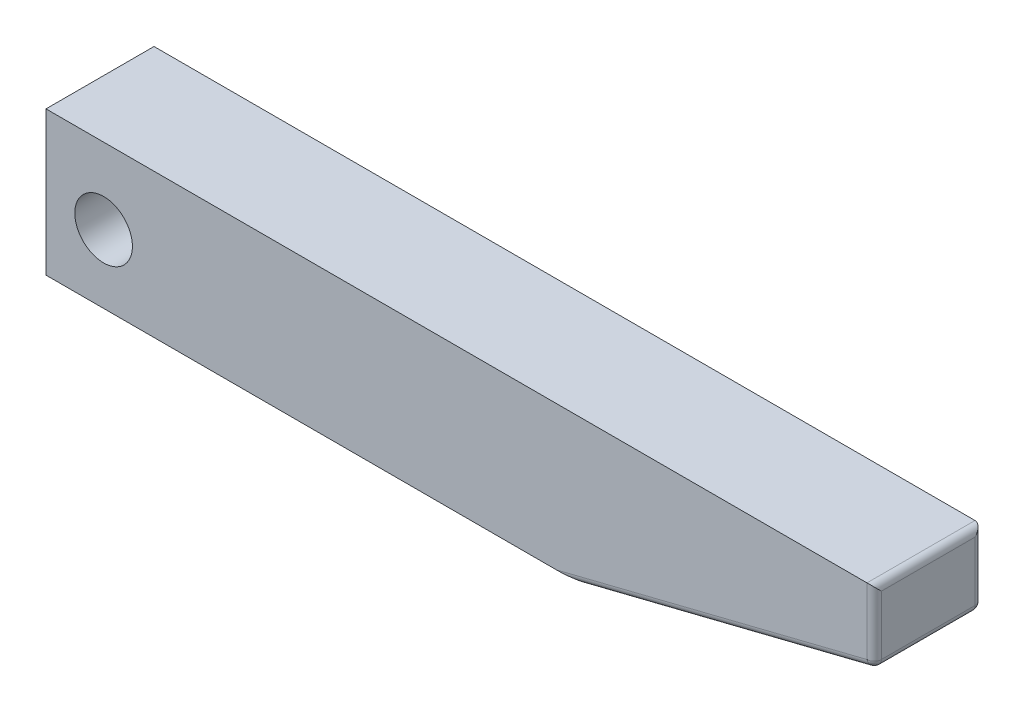
SolidWorks part; units mm, degrees
ref_plane "Alzado" through (0, 0, 0) normal (0, 0, 1) x (1, 0, 0)
ref_plane "Planta" through (0, 0, 0) normal (0, 1, 0) x (1, 0, 0)
ref_plane "Vista lateral" through (0, 0, 0) normal (1, 0, 0) x (0, 0, -1)
sketch "Croquis1" plane through (0, 0, 0) normal (0, 1, 0) x (1, 0, 0)
  line L0 (0, 0.075) -> (1.15, 0.075)
  line L1 (1.15, 0.075) -> (1.15, -0.075)
  line L2 (1.15, -0.075) -> (0, -0.075)
  line L3 (0, -0.075) -> (0, 0.075)
  point P2 (0, 0)
  dimension "D1" = 0.15
  dimension "D2" = 0
  dimension "D3" = 1.15
  dimension "D4" = 0
extrude "Saliente-Extruir2" add sketch "Croquis1" along normal blind 0.2
sketch "Croquis2" plane through (0, 0, 0.075) normal (0, 0, 1) x (1, 0, 0)
  line L0 (0.75, 0) -> (1.15, 0.1)
  line L1 (0, 0) -> (1.15, 0) construction
  line L2 (1.15, 0.2) -> (1.15, 0) construction
  line L3 (1.15, 0.1) -> (1.15, 0)
  line L4 (1.15, 0) -> (0.75, 0)
  dimension "D1" = 0.4
extrude "Cortar-Extruir1" cut sketch "Croquis2" against normal through all
fillet "Redondeo1" radius 0.01 7 edges at (1.15, 0.2, 0) (1.15, 0.15, -0.075) (1.15, 0.1, 0) (1.15, 0.15, 0.075) (0.75, 0, 0) (0.95, 0.05, -0.075) (0.95, 0.05, 0.075)
sketch "Croquis3" plane through (0, 0, 0.075) normal (0, 0, 1) x (1, 0, 0)
  line L0 (0, 0.2) -> (0, 0) construction
  circle A0 centre (0.08, 0.0947) radius 0.04
  dimension "D1" = 0.08
  dimension "D2" = 0.08
extrude "Cortar-Extruir2" cut sketch "Croquis3" against normal through all
